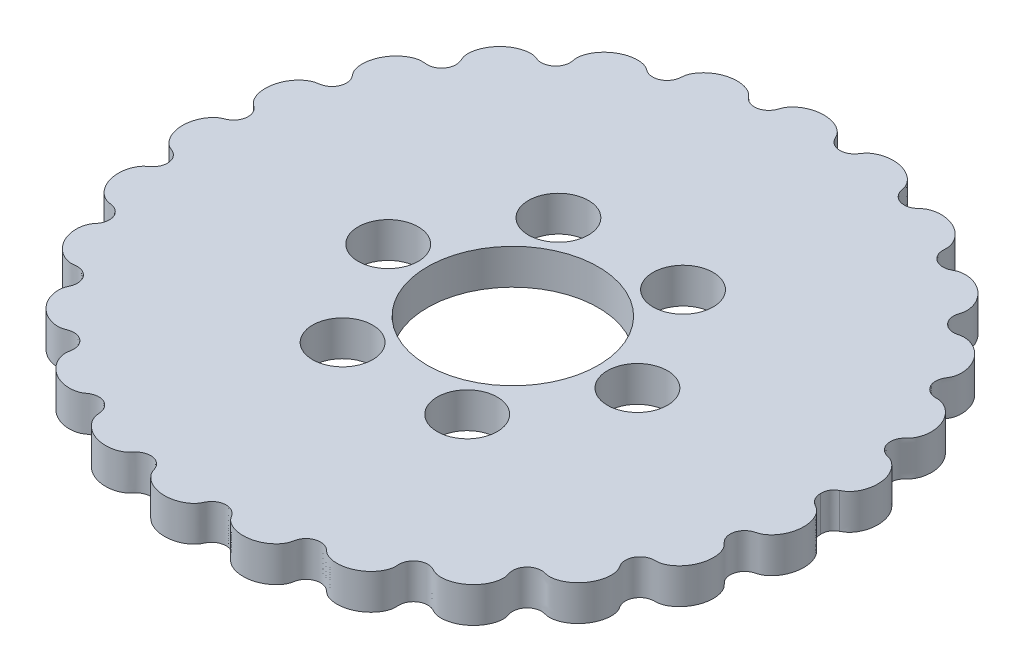
SolidWorks part; units mm, degrees
ref_plane "Front Plane" through (0, 0, 0) normal (0, 0, 1) x (1, 0, 0)
ref_plane "Top Plane" through (0, 0, 0) normal (0, 1, 0) x (1, 0, 0)
ref_plane "Right Plane" through (0, 0, 0) normal (1, 0, 0) x (0, 0, -1)
sketch "Sketch4" plane through (0, 0, 0) normal (0, 1, 0) x (1, 0, 0)
  circle A0 centre (0, 0) radius 35.56 construction
  circle A10 centre (0, 0) radius 9.5758
  circle A12 centre (0, 0) radius 13.97 construction
  circle A14 centre (13.97, 0) radius 3.3655
  circle A16 centre (6.985, -12.0984) radius 3.3655
  circle A18 centre (0, 0) radius 9.5758
  circle A19 centre (-6.985, -12.0984) radius 3.3655
  circle A20 centre (0, 0) radius 9.5758
  circle A21 centre (-13.97, 0) radius 3.3655
  circle A22 centre (0, 0) radius 9.5758
  circle A23 centre (-6.985, 12.0984) radius 3.3655
  circle A24 centre (0, 0) radius 9.5758
  circle A25 centre (6.985, 12.0984) radius 3.3655
  circle A26 centre (0, 0) radius 9.5758
  spline S0 degree 4 poles (30.8129, 15.9969) (30.9141, 15.9378) (31.0718, 15.864) (31.2951, 15.7951) (31.5837, 15.7661) (31.8164, 15.7647) (32.0483, 15.7557) (32.2763, 15.713) (32.5221, 15.6333) (32.7813, 15.5182) (33.1215, 15.3212) (33.5166, 15.0085) (33.9139, 14.575) (34.2704, 14.0126) (34.5246, 13.4058) (34.675, 12.7709) (34.7157, 12.1278) (34.6506, 11.5453) (34.4984, 11.0466) (34.2935, 10.6311) (34.0407, 10.321) (33.7456, 10.0779) (33.5414, 9.7749) (33.3742, 9.3841) (33.308, 8.8923) (33.4084, 8.4018) (33.6643, 7.9739) (33.9774, 7.6783) (34.2925, 7.4793) (34.6663, 7.3758) (35.0607, 7.2671) (35.4611, 7.0145) (35.8558, 6.6591) (36.2142, 6.1821) (36.5077, 5.5961) (36.7026, 4.9458) (36.7855, 4.2503) (36.7461, 3.6207) (36.6209, 3.0765) (36.4542, 2.643) (36.2824, 2.3131) (36.0877, 2.0339) (35.8812, 1.8016) (35.6658, 1.6255) (35.4522, 1.5) (35.2361, 1.3783) (35.0366, 1.2323) (34.8625, 1.0548) (34.7163, 0.8535) (34.6002, 0.6342) (34.5191, 0.3891) (34.4748, 0.0815) (34.4779, -0.1246) (34.5375, -0.4902) (34.6586, -0.7606) (34.8456, -1.0436) (35.0937, -1.2963) (35.4145, -1.4784) (35.7504, -1.6681) (36.0112, -1.9406) (36.2272, -2.2259) (36.4389, -2.6009) (36.6233, -3.0662) (36.7503, -3.638) (36.7799, -4.3045) (36.6972, -4.9658) (36.5054, -5.6024) (36.2443, -6.1223) (35.9543, -6.526) (35.6601, -6.8372) (35.383, -7.0612) (35.0661, -7.2635) (34.6965, -7.3712) (34.3404, -7.4598) (34.0359, -7.6384) (33.725, -7.903) (33.4534, -8.2998) (33.3214, -8.7653) (33.3458, -9.2504) (33.4789, -9.6491) (33.6559, -9.9684) (33.9272, -10.2337) (34.2156, -10.5119) (34.4464, -10.9188) (34.6237, -11.4174) (34.7124, -12.0084) (34.6901, -12.6676) (34.5539, -13.3139) (34.313, -13.9279) (33.9732, -14.4935) (33.5955, -14.9306) (33.2185, -15.2497) (32.8604, -15.479) (32.5402, -15.6289) (32.1874, -15.749) (31.8065, -15.7709) (31.4422, -15.7613) (31.1037, -15.8496) (30.7349, -16.0189) (30.3651, -16.3258) (30.1096, -16.739) (30.0007, -17.2155) (30.0217, -17.6398) (30.1087, -17.997) (30.2987, -18.3276) (30.5164, -18.6657) (30.6449, -19.1177) (30.6971, -19.6473) (30.6394, -20.2458) (30.4554, -20.8836) (30.1663, -21.4732) (29.7907, -21.9983) (29.3407, -22.4517) (28.831, -22.8176) (28.312, -23.0712) (27.8121, -23.2081) (27.3454, -23.2611) (26.9374, -23.2056) (26.5694, -23.0886) (26.2092, -23.0846) (25.8104, -23.1523) (25.379, -23.3461) (25.0239, -23.672) (24.7899, -24.1004) (24.6946, -24.5189) (24.6843, -24.8887) (24.7772, -25.2607) (24.9117, -25.6416) (24.9301, -26.1131) (24.8523, -26.6429) (24.6502, -27.2127) (24.3134, -27.7902) (23.8851, -28.2945) (23.3867, -28.7145) (22.8325, -29.0449) (22.2402, -29.2746) (21.674, -29.3883) (21.1617, -29.3949) (20.7113, -29.3313) (20.3479, -29.1871) (19.9656, -28.9536) (19.4728, -28.8295) (18.8929, -28.8708) (18.3849, -29.1258) (18.0401, -29.4775) (17.8329, -29.8589) (17.7248, -30.2147) (17.7124, -30.6005) (17.7544, -31.0041) (17.6611, -31.4689) (17.4563, -31.9673) (17.1203, -32.4741) (16.6491, -32.9548) (16.1085, -33.3396) (15.5218, -33.6241) (14.9056, -33.8075) (14.2789, -33.885) (13.7064, -33.8574) (13.2097, -33.7418) (12.7914, -33.5721) (12.47, -33.3512) (12.1628, -33.0295) (11.7259, -32.779) (11.1593, -32.6628) (10.516, -32.7845) (10.0163, -33.1204) (9.6947, -33.5651) (9.5482, -34.0151) (9.4947, -34.4195) (9.2938, -34.8516) (8.9726, -35.2885) (8.5213, -35.7011) (7.9429, -36.0542) (7.3225, -36.295) (6.6836, -36.4264) (6.0437, -36.4524) (5.4209, -36.375) (4.8763, -36.2097) (4.4237, -35.9797) (4.0616, -35.7153) (3.7982, -35.4287) (3.5842, -35.042) (3.2353, -34.6864) (2.7191, -34.421) (2.0614, -34.3639) (1.4875, -34.5564) (1.0686, -34.8987) (0.8118, -35.2745) (0.6738, -35.6234) (0.4595, -35.9251) (0.198, -36.1791) (-0.1592, -36.4471) (-0.6296, -36.6949) (-1.2194, -36.8877) (-1.9018, -36.9759) (-2.5671, -36.9469) (-3.1981, -36.8138) (-3.7795, -36.5881) (-4.2639, -36.2968) (-4.6469, -35.9668) (-4.9317, -35.6238) (-5.1251, -35.2866) (-5.2326, -34.8608) (-5.4707, -34.4287) (-5.8908, -34.0393) (-6.4958, -33.8069) (-7.1009, -33.8288) (-7.6107, -34.0448) (-7.979, -34.3549) (-8.2202, -34.6922) (-8.5983, -34.9935) (-9.0956, -35.2313) (-9.6948, -35.3862) (-10.3811, -35.4226) (-11.0452, -35.3386) (-11.67, -35.1489) (-12.2407, -34.8688) (-12.7462, -34.51) (-13.1423, -34.1122) (-13.4336, -33.7015) (-13.6259, -33.3019) (-13.7371, -32.9295) (-13.7362, -32.4932) (-13.8473, -32.0178) (-14.149, -31.5282) (-14.6766, -31.1361) (-15.28, -30.9977) (-15.843, -31.0821) (-16.2828, -31.2989) (-16.6034, -31.5678) (-17.0481, -31.7601) (-17.5868, -31.8636) (-18.2014, -31.8616) (-18.8674, -31.7265) (-19.4775, -31.4849) (-20.0204, -31.1578) (-20.488, -30.7655) (-20.8768, -30.3229) (-21.1661, -29.8604) (-21.3639, -29.3961) (-21.4689, -28.9494) (-21.5035, -28.5286) (-21.4109, -28.1547) (-21.3776, -27.8066) (-21.4236, -27.4224) (-21.5774, -26.9872) (-21.9325, -26.5306) (-22.4732, -26.2343) (-23.0422, -26.1647) (-23.5276, -26.2556) (-23.9076, -26.4368) (-24.3017, -26.5094) (-24.682, -26.5052) (-25.1226, -26.4466) (-25.6141, -26.3028) (-26.1534, -26.0452) (-26.6869, -25.6591) (-27.1327, -25.2088) (-27.4883, -24.7148) (-27.7553, -24.194) (-27.9221, -23.6778) (-28.0016, -23.1814) (-27.9954, -22.7239) (-27.9301, -22.3069) (-27.752, -21.9673) (-27.6281, -21.643) (-27.5714, -21.2652) (-27.6022, -20.808) (-27.8195, -20.274) (-28.2604, -19.8407) (-28.7929, -19.6206) (-29.2886, -19.5766) (-29.7045, -19.6566) (-30.1065, -19.6387) (-30.4773, -19.5407) (-30.8928, -19.3774) (-31.3373, -19.1162) (-31.7997, -18.7327) (-32.2543, -18.1884) (-32.6144, -17.5524) (-32.8254, -16.9303) (-32.9165, -16.3568) (-32.9219, -15.8741) (-32.8809, -15.4896) (-32.7971, -15.1482) (-32.6834, -14.8507) (-32.5411, -14.6069) (-32.3843, -14.4151) (-32.2301, -14.2205) (-32.1046, -14.0067) (-32.0132, -13.7756) (-31.957, -13.5335) (-31.9281, -13.1557) (-32.0222, -12.647) (-32.3215, -12.1636) (-32.8139, -11.8162) (-33.2951, -11.67) (-33.708, -11.6461) (-34.1599, -11.4866) (-34.6219, -11.1962) (-35.068, -10.779) (-35.4624, -10.2281) (-35.7633, -9.5969) (-35.9528, -8.8985) (-36.0042, -8.2498) (-35.9527, -7.6751) (-35.8414, -7.2088) (-35.7097, -6.8479) (-35.5475, -6.5387) (-35.3676, -6.2786) (-35.1741, -6.0755) (-34.9778, -5.9269) (-34.7798, -5.7797) (-34.6023, -5.6091) (-34.4157, -5.3632) (-34.2645, -5.0528) (-34.1806, -4.68) (-34.2013, -4.1673) (-34.3758, -3.6989) (-34.6969, -3.3074) (-35.1236, -3.0338) (-35.5208, -2.9082) (-35.9259, -2.6474) (-36.3061, -2.25) (-36.6397, -1.735) (-36.8884, -1.1001) (-37.0248, -0.4162) (-37.037, 0.3007) (-36.9313, 0.9322) (-36.7485, 1.4656) (-36.5361, 1.8831) (-36.3295, 2.1964) (-36.1055, 2.4573) (-35.8744, 2.6696) (-35.6414, 2.8283) (-35.4142, 2.9354) (-35.18, 3.0266) (-34.957, 3.1409) (-34.755, 3.2913) (-34.5774, 3.4697) (-34.409, 3.7006) (-34.27, 3.9902) (-34.1648, 4.431) (-34.2057, 4.9325) (-34.4119, 5.3969) (-34.751, 5.779) (-35.107, 6.001) (-35.4431, 6.3499) (-35.7169, 6.8318) (-35.9171, 7.4149) (-36.0028, 8.0956) (-35.9669, 8.7932) (-35.8022, 9.4907) (-35.5456, 10.0747) (-35.2399, 10.5443) (-34.9343, 10.8952) (-34.6598, 11.1476) (-34.3814, 11.3458) (-34.1081, 11.4955) (-33.846, 11.5951) (-33.6018, 11.6469) (-33.3537, 11.6757) (-33.1097, 11.7258) (-32.8763, 11.8159) (-32.6585, 11.9391) (-32.4345, 12.1152) (-32.2221, 12.3563) (-32.001, 12.7527) (-31.9043, 13.2492) (-31.9791, 13.7539) (-32.2049, 14.2164) (-32.4936, 14.5244) (-32.7015, 14.867) (-32.8207, 15.2322) (-32.9111, 15.6688) (-32.9332, 16.1848) (-32.8624, 16.7816) (-32.6522, 17.457) (-32.3159, 18.1005) (-31.9125, 18.6115) (-31.4876, 18.9962) (-31.0921, 19.2624) (-30.7532, 19.4379) (-30.4287, 19.5559) (-30.1268, 19.6253) (-29.8546, 19.6494) (-29.6184, 19.6342) (-29.3837, 19.6014) (-29.1473, 19.5926) (-28.9114, 19.6203) (-28.6817, 19.6804) (-28.4277, 19.7875) (-28.1631, 19.9596) (-27.8446, 20.2798) (-27.616, 20.7342) (-27.5533, 21.2424) (-27.647, 21.7523) (-27.8488, 22.1263) (-27.974, 22.5095) (-28.0008, 22.8957) (-27.9833, 23.3434) (-27.8781, 23.8518) (-27.6624, 24.4158) (-27.2888, 25.0246) (-26.7962, 25.5727) (-26.2681, 25.9728) (-25.7469, 26.2434) (-25.2862, 26.4002) (-24.9028, 26.4859) (-24.5026, 26.5098) (-24.0748, 26.4929) (-23.6747, 26.321) (-23.2467, 26.182) (-22.803, 26.1894) (-22.3941, 26.2938) (-21.9513, 26.5462) (-21.6066, 26.9253) (-21.4079, 27.4079) (-21.3671, 27.9354) (-21.4719, 28.3605) (-21.4966, 28.7721) (-21.424, 29.1561) (-21.292, 29.5842) (-21.0649, 30.0442) (-20.7183, 30.5307) (-20.214, 31.0189) (-19.6163, 31.4197) (-19.0241, 31.6742) (-18.4738, 31.8096) (-18.0048, 31.8568) (-17.6275, 31.8522) (-17.2893, 31.8051) (-16.9935, 31.727) (-16.7431, 31.6257) (-16.5422, 31.5069) (-16.3545, 31.3672) (-16.158, 31.2405) (-15.9451, 31.1433) (-15.7202, 31.0771) (-15.4489, 31.0372) (-15.1332, 31.0467) (-14.6921, 31.1557) (-14.2548, 31.4308) (-13.9343, 31.8439) (-13.7527, 32.345) (-13.7437, 32.7851) (-13.6744, 33.1938) (-13.5087, 33.551) (-13.2764, 33.9362) (-12.942, 34.3287) (-12.4849, 34.7172) (-11.8747, 35.067) (-11.1973, 35.308) (-10.4694, 35.4237) (-9.8108, 35.398) (-9.2592, 35.2766) (-8.8571, 35.1152) (-8.5903, 34.9692) (-8.3721, 34.8126) (-8.2053, 34.6514) (-8.0584, 34.4712) (-7.9028, 34.2984) (-7.725, 34.1487) (-7.5272, 34.0255) (-7.2773, 33.9146) (-6.9708, 33.8388) (-6.5161, 33.825) (-6.0189, 33.9732) (-5.5983, 34.2872) (-5.2881, 34.7247) (-5.1634, 35.1496) (-5.0027, 35.5342) (-4.7524, 35.8422) (-4.494, 36.1011) (-4.2212, 36.3113) (-3.8569, 36.5378) (-3.3867, 36.7504) (-2.6114, 36.967) (-1.699, 36.9946) (-0.883, 36.8152) (-0.2129, 36.4811) (0.1365, 36.2288) (0.3591, 36.0241) (0.5332, 35.8215) (0.6571, 35.627) (0.7555, 35.4179) (0.8602, 35.2117) (0.9906, 35.021) (1.1474, 34.8505) (1.3579, 34.6772) (1.6326, 34.5219) (2.0672, 34.3864) (2.588, 34.3959) (3.0788, 34.5871) (3.4963, 34.9285) (3.7298, 35.3078) (3.9747, 35.6478) (4.295, 35.8871) (4.6095, 36.0769) (4.9269, 36.2148) (5.3372, 36.346) (5.8476, 36.4371) (6.4661, 36.452) (7.1758, 36.3402) (7.8661, 36.0967) (8.4278, 35.7651) (8.8519, 35.4018) (9.1286, 35.0743) (9.2945, 34.8236) (9.4149, 34.5867) (9.4897, 34.3699) (9.5349, 34.1446) (9.5825, 33.9195) (9.6568, 33.7021) (9.7618, 33.4972) (9.9179, 33.2745) (10.1407, 33.0514) (10.5234, 32.8041) (11.0292, 32.6735) (11.555, 32.7271) (12.0506, 32.9469) (12.378, 33.2524) (12.6955, 33.5295) (13.0669, 33.6847) (13.4194, 33.7935) (13.7625, 33.85) (14.1944, 33.8772) (14.7137, 33.8402) (15.3182, 33.7021) (15.9775, 33.4192) (16.586, 33.0146) (17.0452, 32.5582) (17.3693, 32.1048) (17.5779, 31.6711) (17.7155, 31.2767) (17.7523, 30.842) (17.6929, 30.3843) (17.7887, 29.9663) (17.9535, 29.6169) (18.2228, 29.2813) (18.5403, 29.0441) (18.9103, 28.8971) (19.3021, 28.8494) (19.6184, 28.8731) (19.949, 28.9593) (20.2685, 29.1346) (20.6143, 29.3106) (21.0258, 29.3789) (21.4771, 29.3985) (21.9718, 29.335) (22.6298, 29.1487) (23.3015, 28.7935) (23.9084, 28.2921) (24.356, 27.72) (24.6105, 27.2653) (24.7697, 26.8624) (24.8642, 26.5275) (24.9156, 26.1618) (24.9325, 25.7593) (24.816, 25.3537) (24.6788, 24.927) (24.6922, 24.4846) (24.8019, 24.0762) (25.0619, 23.6326) (25.4098, 23.3278) (25.7929, 23.1565) (26.1587, 23.0946) (26.3888, 23.0876) (26.6167, 23.1138) (26.8403, 23.1669) (27.0633, 23.2214) (27.2912, 23.2453) (27.5564, 23.2366) (27.8536, 23.1928) (28.2671, 23.0814) (28.7757, 22.8521) (29.314, 22.485) (29.8276, 21.9641) (30.2306, 21.3694) (30.4803, 20.8031) (30.6149, 20.3019) (30.6706, 19.8744) (30.6807, 19.5281) (30.6422, 19.1625) (30.5617, 18.7703) (30.3562, 18.4046) (30.1138, 18.0305) (29.9836, 17.5067) (30.0299, 16.88) (30.3155, 16.363) (30.7137, 16.0328) (31.0511, 15.8745) (31.272, 15.8062) (31.4999, 15.7703) (31.7308, 15.7639) (31.9617, 15.7635) (32.1901, 15.7335) (32.4471, 15.6617) (32.7265, 15.5471) (33.1029, 15.338) (33.6894, 14.8738) (34.1984, 14.212) (34.5613, 13.3748) (34.695, 12.581) (34.7025, 12.0645) (34.6522, 11.6382) (34.5779, 11.3016) (34.453, 10.9575) (34.2804, 10.5994) (33.999, 10.2914) (33.6683, 9.9961) (33.4053, 9.5281) (33.2832, 8.9139) (33.4194, 8.3408) (33.7142, 7.9157) (33.9973, 7.6726) (34.1931, 7.5471) (34.4044, 7.4509) (34.6269, 7.3843) (34.8522, 7.3279) (35.0686, 7.245) (35.3026, 7.1138) (35.5477, 6.9343) (35.7957, 6.7031) (36.0361, 6.4153) (36.2946, 6.0249) (36.5371, 5.5166) (36.7002, 4.9528) (36.7708, 4.3485) (36.7568, 3.8123) (36.6888, 3.3519) (36.5634, 2.9036) (36.4022, 2.5293) (36.2258, 2.2283) (36.051, 1.9952) (35.8966, 1.8225) (35.7289, 1.6708) (35.5159, 1.5314) (35.2526, 1.3933) (35.0533, 1.2484) (34.6934, 0.8863) (34.5576, 0.5221) (34.4501, 0.0873) (34.4947, -0.2833) (34.5888, -0.6209) (34.7387, -0.8968) (34.9548, -1.1657) (35.2472, -1.4039) (35.6205, -1.5717) (35.9512, -1.8607) (36.2466, -2.2426) (36.4952, -2.7074) (36.6754, -3.2518) (36.7697, -3.8616) (36.7655, -4.4834) (36.6639, -5.0999) (36.4641, -5.6975) (36.1658, -6.2558) (35.8091, -6.7076) (35.4217, -7.0433) (35.0313, -7.2789) (34.6501, -7.3779) (34.2911, -7.4826) (33.986, -7.6726) (33.6802, -7.9562) (33.4219, -8.3705) (33.3115, -8.8509) (33.3633, -9.34) (33.5203, -9.7354) (33.7163, -10.0454) (34.0075, -10.2937) (34.2724, -10.5945) (34.4457, -10.9378) (34.5702, -11.2754) (34.6644, -11.6881) (34.7111, -12.1695) (34.6799, -12.735) (34.5347, -13.3769) (34.2793, -13.998) (33.9153, -14.5758) (33.4428, -15.0891) (32.8874, -15.4894) (32.4132, -15.6918) (32.083, -15.7522) (31.92, -15.7618) knots 0 0 0 0 0 0.001475 0.002213 0.002951 0.003689 0.004426 0.005164 0.005902 0.006966 0.00803 0.010158 0.012286 0.014414 0.016458 0.018502 0.020546 0.022589 0.023857 0.025124 0.026391 0.027658 0.028688 0.029718 0.031779 0.033863 0.034905 0.035947 0.037241 0.038535 0.039829 0.041123 0.043201 0.045279 0.047357 0.049435 0.051795 0.054155 0.055335 0.056515 0.057695 0.058875 0.059661 0.060448 0.061234 0.062021 0.062807 0.063594 0.06438 0.065167 0.066002 0.066837 0.067842 0.068848 0.069854 0.070859 0.072083 0.073307 0.074532 0.075756 0.076814 0.077873 0.07999 0.082108 0.084225 0.086328 0.088432 0.090535 0.091586 0.092638 0.09386 0.095082 0.096303 0.097525 0.098517 0.099509 0.101493 0.10353 0.104549 0.105568 0.106835 0.108103 0.10937 0.110638 0.112729 0.11482 0.116911 0.119001 0.121091 0.12318 0.12527 0.126314 0.127359 0.128571 0.129782 0.130993 0.132205 0.133191 0.134176 0.136148 0.138211 0.139242 0.140274 0.141545 0.142817 0.144088 0.145359 0.147464 0.149568 0.151673 0.153778 0.15577 0.157763 0.159756 0.161748 0.163054 0.16436 0.165666 0.166972 0.16793 0.168888 0.170804 0.17289 0.173934 0.174977 0.176253 0.177528 0.178804 0.180079 0.182198 0.184317 0.186435 0.188554 0.19057 0.192585 0.194601 0.196617 0.197857 0.199097 0.200337 0.201576 0.203518 0.205459 0.207568 0.208623 0.209677 0.210958 0.212239 0.213519 0.2148 0.216932 0.219064 0.221196 0.223329 0.225331 0.227334 0.229336 0.231339 0.232573 0.233807 0.235041 0.236275 0.238195 0.240115 0.242246 0.244376 0.245662 0.246949 0.248235 0.249522 0.251667 0.253813 0.255958 0.258104 0.260093 0.262082 0.264072 0.266061 0.26729 0.26852 0.269749 0.270978 0.272876 0.274774 0.276967 0.279161 0.280347 0.281533 0.282719 0.283904 0.285026 0.286148 0.288392 0.290636 0.29288 0.294856 0.296832 0.298808 0.300785 0.30201 0.303236 0.304462 0.305687 0.307561 0.309435 0.311584 0.313733 0.315041 0.316349 0.317657 0.318964 0.321137 0.32331 0.325483 0.327656 0.329619 0.331582 0.333545 0.335508 0.336731 0.337954 0.339177 0.3404 0.342249 0.344098 0.346328 0.348558 0.349877 0.351196 0.352515 0.353834 0.355984 0.358133 0.360283 0.362433 0.364298 0.366164 0.368029 0.369895 0.371219 0.372544 0.373869 0.375194 0.376086 0.376978 0.378762 0.381008 0.383254 0.38458 0.385907 0.387234 0.388561 0.389642 0.390723 0.392885 0.395046 0.397208 0.399062 0.400916 0.402769 0.404623 0.405947 0.40727 0.408594 0.409918 0.410795 0.411673 0.413428 0.415688 0.417948 0.419283 0.420618 0.421953 0.423288 0.424375 0.425462 0.427636 0.42981 0.431984 0.434437 0.43689 0.438117 0.439343 0.44057 0.441796 0.442584 0.443371 0.444159 0.444946 0.445734 0.446521 0.447308 0.448096 0.450538 0.45298 0.454283 0.455586 0.456889 0.458191 0.460333 0.462475 0.464617 0.466759 0.469196 0.471633 0.472851 0.474069 0.475288 0.476506 0.477289 0.478071 0.478853 0.479636 0.480418 0.481201 0.482766 0.483992 0.485218 0.487671 0.488983 0.490295 0.491607 0.492919 0.495073 0.497226 0.49938 0.501534 0.503915 0.506296 0.507487 0.508678 0.509868 0.511059 0.511856 0.512653 0.513451 0.514248 0.515045 0.515843 0.51664 0.517437 0.518668 0.519899 0.522361 0.523683 0.525004 0.526326 0.527647 0.529812 0.531978 0.534143 0.536308 0.538674 0.54104 0.542223 0.543406 0.544589 0.545772 0.546564 0.547357 0.548149 0.548942 0.549734 0.550527 0.551319 0.552112 0.553347 0.554582 0.557053 0.558384 0.559715 0.561047 0.562378 0.563466 0.564554 0.56673 0.568906 0.571082 0.573504 0.575926 0.577137 0.578348 0.579559 0.580771 0.581523 0.582276 0.583028 0.583781 0.584533 0.585286 0.586038 0.586791 0.58803 0.589269 0.591747 0.593088 0.594429 0.59577 0.597111 0.598204 0.599298 0.601484 0.603671 0.605857 0.608335 0.610813 0.612052 0.613291 0.61453 0.615769 0.617195 0.618621 0.620046 0.621472 0.622718 0.623965 0.626458 0.627839 0.62922 0.630601 0.631982 0.633064 0.634145 0.636307 0.63847 0.640633 0.643028 0.645423 0.646621 0.647818 0.649016 0.650213 0.650956 0.651699 0.652442 0.653185 0.653927 0.65467 0.655413 0.656156 0.657406 0.658657 0.661158 0.662548 0.663938 0.665328 0.666718 0.667804 0.66889 0.671063 0.673235 0.675407 0.67779 0.680172 0.682554 0.683745 0.684936 0.685675 0.686413 0.687151 0.68789 0.688628 0.689366 0.690104 0.690843 0.692097 0.69335 0.695858 0.697257 0.698657 0.700056 0.701456 0.702547 0.703637 0.704728 0.705819 0.708001 0.710182 0.714921 0.717291 0.718475 0.71966 0.720394 0.721128 0.721862 0.722596 0.72333 0.724065 0.724799 0.725533 0.726789 0.728046 0.730559 0.731967 0.733376 0.734784 0.736192 0.737288 0.738384 0.739479 0.740575 0.742766 0.744957 0.747314 0.749671 0.752028 0.753206 0.754385 0.755115 0.755845 0.756575 0.757305 0.758035 0.758765 0.759495 0.760226 0.761484 0.762743 0.765261 0.766678 0.768095 0.769511 0.770928 0.772029 0.773129 0.77423 0.77533 0.777531 0.779732 0.782077 0.784421 0.786766 0.787938 0.78911 0.790563 0.792016 0.793469 0.794921 0.795916 0.79691 0.798898 0.7999 0.800903 0.801905 0.802908 0.804215 0.805522 0.806829 0.808136 0.809979 0.811822 0.815509 0.817712 0.819915 0.821016 0.822118 0.823219 0.824321 0.825739 0.827158 0.828576 0.829994 0.831254 0.832513 0.835032 0.835761 0.83649 0.83722 0.837949 0.838678 0.839408 0.840137 0.840866 0.842044 0.843221 0.845575 0.84793 0.850284 0.852477 0.854671 0.855767 0.856864 0.85796 0.859057 0.860467 0.861877 0.863287 0.864697 0.867211 0.869725 0.870458 0.871192 0.871925 0.872658 0.873391 0.874125 0.874858 0.875591 0.876775 0.877958 0.880325 0.885059 0.887243 0.889426 0.890518 0.891609 0.892701 0.893793 0.895194 0.896595 0.897997 0.899398 0.901907 0.904415 0.905153 0.90589 0.906628 0.907365 0.908103 0.90884 0.909578 0.910315 0.911505 0.912695 0.913885 0.915075 0.917454 0.919834 0.921311 0.922788 0.924266 0.925743 0.92722 0.927959 0.928697 0.929436 0.930175 0.930913 0.931652 0.933071 0.934491 0.93591 0.93733 0.938324 0.939318 0.940311 0.941305 0.94269 0.944075 0.94546 0.946845 0.948802 0.950759 0.952715 0.954672 0.956679 0.958686 0.960693 0.9627 0.963946 0.965192 0.966438 0.967684 0.968695 0.969706 0.971728 0.97379 0.974821 0.975853 0.977124 0.978394 0.979665 0.980936 0.98196 0.982984 0.985031 0.987079 0.989126 0.991329 0.993532 0.995735 0.997939 1 1 1 1 1 construction
  spline S1 degree 4 poles (34.4805, 0) (34.4805, -0.0683) (34.4908, -0.2039) (34.5375, -0.4902) (34.6586, -0.7606) (34.8456, -1.0436) (35.0937, -1.2963) (35.4145, -1.4784) (35.7504, -1.6681) (36.0112, -1.9406) (36.2272, -2.2259) (36.4389, -2.6009) (36.6233, -3.0662) (36.7503, -3.638) (36.7799, -4.3045) (36.6972, -4.9658) (36.5054, -5.6024) (36.2443, -6.1223) (35.9543, -6.526) (35.6601, -6.8372) (35.383, -7.0612) (35.0661, -7.2635) (34.6965, -7.3712) (34.3404, -7.4598) (34.0359, -7.6384) (33.725, -7.903) (33.4534, -8.2998) (33.3214, -8.7653) (33.3458, -9.2504) (33.4789, -9.6491) (33.6559, -9.9684) (33.9272, -10.2337) (34.2156, -10.5119) (34.4464, -10.9188) (34.6237, -11.4174) (34.7124, -12.0084) (34.6901, -12.6676) (34.5539, -13.3139) (34.313, -13.9279) (33.9732, -14.4935) (33.5955, -14.9306) (33.2185, -15.2497) (32.8604, -15.479) (32.5402, -15.6289) (32.1874, -15.749) (31.8065, -15.7709) (31.4422, -15.7613) (31.1037, -15.8496) (30.7349, -16.0189) (30.3651, -16.3258) (30.1096, -16.739) (30.0007, -17.2155) (30.0217, -17.6398) (30.1087, -17.997) (30.2987, -18.3276) (30.5164, -18.6657) (30.6449, -19.1177) (30.6971, -19.6473) (30.6394, -20.2458) (30.4554, -20.8836) (30.1663, -21.4732) (29.7907, -21.9983) (29.3407, -22.4517) (28.831, -22.8176) (28.312, -23.0712) (27.8121, -23.2081) (27.3454, -23.2611) (26.9374, -23.2056) (26.5694, -23.0886) (26.2092, -23.0846) (25.8104, -23.1523) (25.379, -23.3461) (25.0239, -23.672) (24.7899, -24.1004) (24.6946, -24.5189) (24.6843, -24.8887) (24.7772, -25.2607) (24.9117, -25.6416) (24.9301, -26.1131) (24.8523, -26.6429) (24.6502, -27.2127) (24.3134, -27.7902) (23.8851, -28.2945) (23.3867, -28.7145) (22.8325, -29.0449) (22.2402, -29.2746) (21.674, -29.3883) (21.1617, -29.3949) (20.7113, -29.3313) (20.3479, -29.1871) (19.9656, -28.9536) (19.4728, -28.8295) (18.8929, -28.8708) (18.3849, -29.1258) (18.0401, -29.4775) (17.8329, -29.8589) (17.7248, -30.2147) (17.7124, -30.6005) (17.7544, -31.0041) (17.6611, -31.4689) (17.4563, -31.9673) (17.1203, -32.4741) (16.6491, -32.9548) (16.1085, -33.3396) (15.5218, -33.6241) (14.9056, -33.8075) (14.2789, -33.885) (13.7064, -33.8574) (13.2097, -33.7418) (12.7914, -33.5721) (12.47, -33.3512) (12.1628, -33.0295) (11.7259, -32.779) (11.1593, -32.6628) (10.516, -32.7845) (10.0163, -33.1204) (9.6947, -33.5651) (9.5482, -34.0151) (9.4947, -34.4195) (9.2938, -34.8516) (8.9726, -35.2885) (8.5213, -35.7011) (7.9429, -36.0542) (7.3225, -36.295) (6.6836, -36.4264) (6.0437, -36.4524) (5.4209, -36.375) (4.8763, -36.2097) (4.4237, -35.9797) (4.0616, -35.7153) (3.7982, -35.4287) (3.5842, -35.042) (3.2353, -34.6864) (2.7191, -34.421) (2.0614, -34.3639) (1.4875, -34.5564) (1.0686, -34.8987) (0.8118, -35.2745) (0.6738, -35.6234) (0.4595, -35.9251) (0.198, -36.1791) (-0.1592, -36.4471) (-0.6296, -36.6949) (-1.2194, -36.8877) (-1.9018, -36.9759) (-2.5671, -36.9469) (-3.1981, -36.8138) (-3.7795, -36.5881) (-4.2639, -36.2968) (-4.6469, -35.9668) (-4.9317, -35.6238) (-5.1251, -35.2866) (-5.2326, -34.8608) (-5.4707, -34.4287) (-5.8908, -34.0393) (-6.4958, -33.8069) (-7.1009, -33.8288) (-7.6107, -34.0448) (-7.979, -34.3549) (-8.2202, -34.6922) (-8.5983, -34.9935) (-9.0956, -35.2313) (-9.6948, -35.3862) (-10.3811, -35.4226) (-11.0452, -35.3386) (-11.67, -35.1489) (-12.2407, -34.8688) (-12.7462, -34.51) (-13.1423, -34.1122) (-13.4336, -33.7015) (-13.6259, -33.3019) (-13.7371, -32.9295) (-13.7362, -32.4932) (-13.8473, -32.0178) (-14.149, -31.5282) (-14.6766, -31.1361) (-15.28, -30.9977) (-15.843, -31.0821) (-16.2828, -31.2989) (-16.6034, -31.5678) (-17.0481, -31.7601) (-17.5868, -31.8636) (-18.2014, -31.8616) (-18.8674, -31.7265) (-19.4775, -31.4849) (-20.0204, -31.1578) (-20.488, -30.7655) (-20.8768, -30.3229) (-21.1661, -29.8604) (-21.3639, -29.3961) (-21.4689, -28.9494) (-21.5035, -28.5286) (-21.4109, -28.1547) (-21.3776, -27.8066) (-21.4236, -27.4224) (-21.5774, -26.9872) (-21.9325, -26.5306) (-22.4732, -26.2343) (-23.0422, -26.1647) (-23.5276, -26.2556) (-23.9076, -26.4368) (-24.3017, -26.5094) (-24.682, -26.5052) (-25.1226, -26.4466) (-25.6141, -26.3028) (-26.1534, -26.0452) (-26.6869, -25.6591) (-27.1327, -25.2088) (-27.4883, -24.7148) (-27.7553, -24.194) (-27.9221, -23.6778) (-28.0016, -23.1814) (-27.9954, -22.7239) (-27.9301, -22.3069) (-27.752, -21.9673) (-27.6281, -21.643) (-27.5714, -21.2652) (-27.6022, -20.808) (-27.8195, -20.274) (-28.2604, -19.8407) (-28.7929, -19.6206) (-29.2886, -19.5766) (-29.7045, -19.6566) (-30.1065, -19.6387) (-30.4773, -19.5407) (-30.8928, -19.3774) (-31.3373, -19.1162) (-31.7997, -18.7327) (-32.2543, -18.1884) (-32.6144, -17.5524) (-32.8254, -16.9303) (-32.9165, -16.3568) (-32.9219, -15.8741) (-32.8809, -15.4896) (-32.7971, -15.1482) (-32.6834, -14.8507) (-32.5411, -14.6069) (-32.3843, -14.4151) (-32.2301, -14.2205) (-32.1046, -14.0067) (-32.0132, -13.7756) (-31.957, -13.5335) (-31.9281, -13.1557) (-32.0222, -12.647) (-32.3215, -12.1636) (-32.8139, -11.8162) (-33.2951, -11.67) (-33.708, -11.6461) (-34.1599, -11.4866) (-34.6219, -11.1962) (-35.068, -10.779) (-35.4624, -10.2281) (-35.7633, -9.5969) (-35.9528, -8.8985) (-36.0042, -8.2498) (-35.9527, -7.6751) (-35.8414, -7.2088) (-35.7097, -6.8479) (-35.5475, -6.5387) (-35.3676, -6.2786) (-35.1741, -6.0755) (-34.9778, -5.9269) (-34.7798, -5.7797) (-34.6023, -5.6091) (-34.4157, -5.3632) (-34.2645, -5.0528) (-34.1806, -4.68) (-34.2013, -4.1673) (-34.3758, -3.6989) (-34.6969, -3.3074) (-35.1236, -3.0338) (-35.5208, -2.9082) (-35.9259, -2.6474) (-36.3061, -2.25) (-36.6397, -1.735) (-36.8884, -1.1001) (-37.0248, -0.4162) (-37.037, 0.3007) (-36.9313, 0.9322) (-36.7485, 1.4656) (-36.5361, 1.8831) (-36.3295, 2.1964) (-36.1055, 2.4573) (-35.8744, 2.6696) (-35.6414, 2.8283) (-35.4142, 2.9354) (-35.18, 3.0266) (-34.957, 3.1409) (-34.755, 3.2913) (-34.5774, 3.4697) (-34.409, 3.7006) (-34.27, 3.9902) (-34.1648, 4.431) (-34.2057, 4.9325) (-34.4119, 5.3969) (-34.751, 5.779) (-35.107, 6.001) (-35.4431, 6.3499) (-35.7169, 6.8318) (-35.9171, 7.4149) (-36.0028, 8.0956) (-35.9669, 8.7932) (-35.8022, 9.4907) (-35.5456, 10.0747) (-35.2399, 10.5443) (-34.9343, 10.8952) (-34.6598, 11.1476) (-34.3814, 11.3458) (-34.1081, 11.4955) (-33.846, 11.5951) (-33.6018, 11.6469) (-33.3537, 11.6757) (-33.1097, 11.7258) (-32.8763, 11.8159) (-32.6585, 11.9391) (-32.4345, 12.1152) (-32.2221, 12.3563) (-32.001, 12.7527) (-31.9043, 13.2492) (-31.9791, 13.7539) (-32.2049, 14.2164) (-32.4936, 14.5244) (-32.7015, 14.867) (-32.8207, 15.2322) (-32.9111, 15.6688) (-32.9332, 16.1848) (-32.8624, 16.7816) (-32.6522, 17.457) (-32.3159, 18.1005) (-31.9125, 18.6115) (-31.4876, 18.9962) (-31.0921, 19.2624) (-30.7532, 19.4379) (-30.4287, 19.5559) (-30.1268, 19.6253) (-29.8546, 19.6494) (-29.6184, 19.6342) (-29.3837, 19.6014) (-29.1473, 19.5926) (-28.9114, 19.6203) (-28.6817, 19.6804) (-28.4277, 19.7875) (-28.1631, 19.9596) (-27.8446, 20.2798) (-27.616, 20.7342) (-27.5533, 21.2424) (-27.647, 21.7523) (-27.8488, 22.1263) (-27.974, 22.5095) (-28.0008, 22.8957) (-27.9833, 23.3434) (-27.8781, 23.8518) (-27.6624, 24.4158) (-27.2888, 25.0246) (-26.7962, 25.5727) (-26.2681, 25.9728) (-25.7469, 26.2434) (-25.2862, 26.4002) (-24.9028, 26.4859) (-24.5026, 26.5098) (-24.0748, 26.4929) (-23.6747, 26.321) (-23.2467, 26.182) (-22.803, 26.1894) (-22.3941, 26.2938) (-21.9513, 26.5462) (-21.6066, 26.9253) (-21.4079, 27.4079) (-21.3671, 27.9354) (-21.4719, 28.3605) (-21.4966, 28.7721) (-21.424, 29.1561) (-21.292, 29.5842) (-21.0649, 30.0442) (-20.7183, 30.5307) (-20.214, 31.0189) (-19.6163, 31.4197) (-19.0241, 31.6742) (-18.4738, 31.8096) (-18.0048, 31.8568) (-17.6275, 31.8522) (-17.2893, 31.8051) (-16.9935, 31.727) (-16.7431, 31.6257) (-16.5422, 31.5069) (-16.3545, 31.3672) (-16.158, 31.2405) (-15.9451, 31.1433) (-15.7202, 31.0771) (-15.4489, 31.0372) (-15.1332, 31.0467) (-14.6921, 31.1557) (-14.2548, 31.4308) (-13.9343, 31.8439) (-13.7527, 32.345) (-13.7437, 32.7851) (-13.6744, 33.1938) (-13.5087, 33.551) (-13.2764, 33.9362) (-12.942, 34.3287) (-12.4849, 34.7172) (-11.8747, 35.067) (-11.1973, 35.308) (-10.4694, 35.4237) (-9.8108, 35.398) (-9.2592, 35.2766) (-8.8571, 35.1152) (-8.5903, 34.9692) (-8.3721, 34.8126) (-8.2053, 34.6514) (-8.0584, 34.4712) (-7.9028, 34.2984) (-7.725, 34.1487) (-7.5272, 34.0255) (-7.2773, 33.9146) (-6.9708, 33.8388) (-6.5161, 33.825) (-6.0189, 33.9732) (-5.5983, 34.2872) (-5.2881, 34.7247) (-5.1634, 35.1496) (-5.0027, 35.5342) (-4.7524, 35.8422) (-4.494, 36.1011) (-4.2212, 36.3113) (-3.8569, 36.5378) (-3.3867, 36.7504) (-2.6114, 36.967) (-1.699, 36.9946) (-0.883, 36.8152) (-0.2129, 36.4811) (0.1365, 36.2288) (0.3591, 36.0241) (0.5332, 35.8215) (0.6571, 35.627) (0.7555, 35.4179) (0.8602, 35.2117) (0.9906, 35.021) (1.1474, 34.8505) (1.3579, 34.6772) (1.6326, 34.5219) (2.0672, 34.3864) (2.588, 34.3959) (3.0788, 34.5871) (3.4963, 34.9285) (3.7298, 35.3078) (3.9747, 35.6478) (4.295, 35.8871) (4.6095, 36.0769) (4.9269, 36.2148) (5.3372, 36.346) (5.8476, 36.4371) (6.4661, 36.452) (7.1758, 36.3402) (7.8661, 36.0967) (8.4278, 35.7651) (8.8519, 35.4018) (9.1286, 35.0743) (9.2945, 34.8236) (9.4149, 34.5867) (9.4897, 34.3699) (9.5349, 34.1446) (9.5825, 33.9195) (9.6568, 33.7021) (9.7618, 33.4972) (9.9179, 33.2745) (10.1407, 33.0514) (10.5234, 32.8041) (11.0292, 32.6735) (11.555, 32.7271) (12.0506, 32.9469) (12.378, 33.2524) (12.6955, 33.5295) (13.0669, 33.6847) (13.4194, 33.7935) (13.7625, 33.85) (14.1944, 33.8772) (14.7137, 33.8402) (15.3182, 33.7021) (15.9775, 33.4192) (16.586, 33.0146) (17.0452, 32.5582) (17.3693, 32.1048) (17.5779, 31.6711) (17.7155, 31.2767) (17.7523, 30.842) (17.6929, 30.3843) (17.7887, 29.9663) (17.9535, 29.6169) (18.2228, 29.2813) (18.5403, 29.0441) (18.9103, 28.8971) (19.3021, 28.8494) (19.6184, 28.8731) (19.949, 28.9593) (20.2685, 29.1346) (20.6143, 29.3106) (21.0258, 29.3789) (21.4771, 29.3985) (21.9718, 29.335) (22.6298, 29.1487) (23.3015, 28.7935) (23.9084, 28.2921) (24.356, 27.72) (24.6105, 27.2653) (24.7697, 26.8624) (24.8642, 26.5275) (24.9156, 26.1618) (24.9325, 25.7593) (24.816, 25.3537) (24.6788, 24.927) (24.6922, 24.4846) (24.8019, 24.0762) (25.0619, 23.6326) (25.4098, 23.3278) (25.7929, 23.1565) (26.1587, 23.0946) (26.3888, 23.0876) (26.6167, 23.1138) (26.8403, 23.1669) (27.0633, 23.2214) (27.2912, 23.2453) (27.5564, 23.2366) (27.8536, 23.1928) (28.2671, 23.0814) (28.7757, 22.8521) (29.314, 22.485) (29.8276, 21.9641) (30.2306, 21.3694) (30.4803, 20.8031) (30.6149, 20.3019) (30.6706, 19.8744) (30.6807, 19.5281) (30.6422, 19.1625) (30.5617, 18.7703) (30.3562, 18.4046) (30.1138, 18.0305) (29.9836, 17.5067) (30.0299, 16.88) (30.3155, 16.363) (30.7137, 16.0328) (31.0511, 15.8745) (31.272, 15.8062) (31.4999, 15.7703) (31.7308, 15.7639) (31.9617, 15.7635) (32.1901, 15.7335) (32.4471, 15.6617) (32.7265, 15.5471) (33.1029, 15.338) (33.6894, 14.8738) (34.1984, 14.212) (34.5613, 13.3748) (34.695, 12.581) (34.7025, 12.0645) (34.6522, 11.6382) (34.5779, 11.3016) (34.453, 10.9575) (34.2804, 10.5994) (33.999, 10.2914) (33.6683, 9.9961) (33.4053, 9.5281) (33.2832, 8.9139) (33.4194, 8.3408) (33.7142, 7.9157) (33.9973, 7.6726) (34.1931, 7.5471) (34.4044, 7.4509) (34.6269, 7.3843) (34.8522, 7.3279) (35.0686, 7.245) (35.3026, 7.1138) (35.5477, 6.9343) (35.7957, 6.7031) (36.0361, 6.4153) (36.2946, 6.0249) (36.5371, 5.5166) (36.7002, 4.9528) (36.7708, 4.3485) (36.7568, 3.8123) (36.6888, 3.3519) (36.5634, 2.9036) (36.4022, 2.5293) (36.2258, 2.2283) (36.051, 1.9952) (35.8966, 1.8225) (35.7289, 1.6708) (35.5159, 1.5314) (35.3554, 1.4473) (35.2682, 1.3945) (35.2265, 1.3666) knots 0.066837 0.066837 0.066837 0.066837 0.066837 0.067842 0.068848 0.069854 0.070859 0.072083 0.073307 0.074532 0.075756 0.076814 0.077873 0.07999 0.082108 0.084225 0.086328 0.088432 0.090535 0.091586 0.092638 0.09386 0.095082 0.096303 0.097525 0.098517 0.099509 0.101493 0.10353 0.104549 0.105568 0.106835 0.108103 0.10937 0.110638 0.112729 0.11482 0.116911 0.119001 0.121091 0.12318 0.12527 0.126314 0.127359 0.128571 0.129782 0.130993 0.132205 0.133191 0.134176 0.136148 0.138211 0.139242 0.140274 0.141545 0.142817 0.144088 0.145359 0.147464 0.149568 0.151673 0.153778 0.15577 0.157763 0.159756 0.161748 0.163054 0.16436 0.165666 0.166972 0.16793 0.168888 0.170804 0.17289 0.173934 0.174977 0.176253 0.177528 0.178804 0.180079 0.182198 0.184317 0.186435 0.188554 0.19057 0.192585 0.194601 0.196617 0.197857 0.199097 0.200337 0.201576 0.203518 0.205459 0.207568 0.208623 0.209677 0.210958 0.212239 0.213519 0.2148 0.216932 0.219064 0.221196 0.223329 0.225331 0.227334 0.229336 0.231339 0.232573 0.233807 0.235041 0.236275 0.238195 0.240115 0.242246 0.244376 0.245662 0.246949 0.248235 0.249522 0.251667 0.253813 0.255958 0.258104 0.260093 0.262082 0.264072 0.266061 0.26729 0.26852 0.269749 0.270978 0.272876 0.274774 0.276967 0.279161 0.280347 0.281533 0.282719 0.283904 0.285026 0.286148 0.288392 0.290636 0.29288 0.294856 0.296832 0.298808 0.300785 0.30201 0.303236 0.304462 0.305687 0.307561 0.309435 0.311584 0.313733 0.315041 0.316349 0.317657 0.318964 0.321137 0.32331 0.325483 0.327656 0.329619 0.331582 0.333545 0.335508 0.336731 0.337954 0.339177 0.3404 0.342249 0.344098 0.346328 0.348558 0.349877 0.351196 0.352515 0.353834 0.355984 0.358133 0.360283 0.362433 0.364298 0.366164 0.368029 0.369895 0.371219 0.372544 0.373869 0.375194 0.376086 0.376978 0.378762 0.381008 0.383254 0.38458 0.385907 0.387234 0.388561 0.389642 0.390723 0.392885 0.395046 0.397208 0.399062 0.400916 0.402769 0.404623 0.405947 0.40727 0.408594 0.409918 0.410795 0.411673 0.413428 0.415688 0.417948 0.419283 0.420618 0.421953 0.423288 0.424375 0.425462 0.427636 0.42981 0.431984 0.434437 0.43689 0.438117 0.439343 0.44057 0.441796 0.442584 0.443371 0.444159 0.444946 0.445734 0.446521 0.447308 0.448096 0.450538 0.45298 0.454283 0.455586 0.456889 0.458191 0.460333 0.462475 0.464617 0.466759 0.469196 0.471633 0.472851 0.474069 0.475288 0.476506 0.477289 0.478071 0.478853 0.479636 0.480418 0.481201 0.482766 0.483992 0.485218 0.487671 0.488983 0.490295 0.491607 0.492919 0.495073 0.497226 0.49938 0.501534 0.503915 0.506296 0.507487 0.508678 0.509868 0.511059 0.511856 0.512653 0.513451 0.514248 0.515045 0.515843 0.51664 0.517437 0.518668 0.519899 0.522361 0.523683 0.525004 0.526326 0.527647 0.529812 0.531978 0.534143 0.536308 0.538674 0.54104 0.542223 0.543406 0.544589 0.545772 0.546564 0.547357 0.548149 0.548942 0.549734 0.550527 0.551319 0.552112 0.553347 0.554582 0.557053 0.558384 0.559715 0.561047 0.562378 0.563466 0.564554 0.56673 0.568906 0.571082 0.573504 0.575926 0.577137 0.578348 0.579559 0.580771 0.581523 0.582276 0.583028 0.583781 0.584533 0.585286 0.586038 0.586791 0.58803 0.589269 0.591747 0.593088 0.594429 0.59577 0.597111 0.598204 0.599298 0.601484 0.603671 0.605857 0.608335 0.610813 0.612052 0.613291 0.61453 0.615769 0.617195 0.618621 0.620046 0.621472 0.622718 0.623965 0.626458 0.627839 0.62922 0.630601 0.631982 0.633064 0.634145 0.636307 0.63847 0.640633 0.643028 0.645423 0.646621 0.647818 0.649016 0.650213 0.650956 0.651699 0.652442 0.653185 0.653927 0.65467 0.655413 0.656156 0.657406 0.658657 0.661158 0.662548 0.663938 0.665328 0.666718 0.667804 0.66889 0.671063 0.673235 0.675407 0.67779 0.680172 0.682554 0.683745 0.684936 0.685675 0.686413 0.687151 0.68789 0.688628 0.689366 0.690104 0.690843 0.692097 0.69335 0.695858 0.697257 0.698657 0.700056 0.701456 0.702547 0.703637 0.704728 0.705819 0.708001 0.710182 0.714921 0.717291 0.718475 0.71966 0.720394 0.721128 0.721862 0.722596 0.72333 0.724065 0.724799 0.725533 0.726789 0.728046 0.730559 0.731967 0.733376 0.734784 0.736192 0.737288 0.738384 0.739479 0.740575 0.742766 0.744957 0.747314 0.749671 0.752028 0.753206 0.754385 0.755115 0.755845 0.756575 0.757305 0.758035 0.758765 0.759495 0.760226 0.761484 0.762743 0.765261 0.766678 0.768095 0.769511 0.770928 0.772029 0.773129 0.77423 0.77533 0.777531 0.779732 0.782077 0.784421 0.786766 0.787938 0.78911 0.790563 0.792016 0.793469 0.794921 0.795916 0.79691 0.798898 0.7999 0.800903 0.801905 0.802908 0.804215 0.805522 0.806829 0.808136 0.809979 0.811822 0.815509 0.817712 0.819915 0.821016 0.822118 0.823219 0.824321 0.825739 0.827158 0.828576 0.829994 0.831254 0.832513 0.835032 0.835761 0.83649 0.83722 0.837949 0.838678 0.839408 0.840137 0.840866 0.842044 0.843221 0.845575 0.84793 0.850284 0.852477 0.854671 0.855767 0.856864 0.85796 0.859057 0.860467 0.861877 0.863287 0.864697 0.867211 0.869725 0.870458 0.871192 0.871925 0.872658 0.873391 0.874125 0.874858 0.875591 0.876775 0.877958 0.880325 0.885059 0.887243 0.889426 0.890518 0.891609 0.892701 0.893793 0.895194 0.896595 0.897997 0.899398 0.901907 0.904415 0.905153 0.90589 0.906628 0.907365 0.908103 0.90884 0.909578 0.910315 0.911505 0.912695 0.913885 0.915075 0.917454 0.919834 0.921311 0.922788 0.924266 0.925743 0.92722 0.927959 0.928697 0.929436 0.930175 0.930913 0.931652 0.931652 0.931652 0.931652 0.931652
  spline S2 degree 2 poles (35.2265, 1.3666) (34.452, 0.9639) (34.4805, 0) knots 0 0 0 1 1 1
  dimension "D1" = 71.12
  dimension "D6" = 19.1516
  dimension "D7" = 27.94
  dimension "D8" = 6.731
  dimension "D9" = 6
extrude "Boss-Extrude1" add sketch "Sketch4" along normal blind 3.9688
